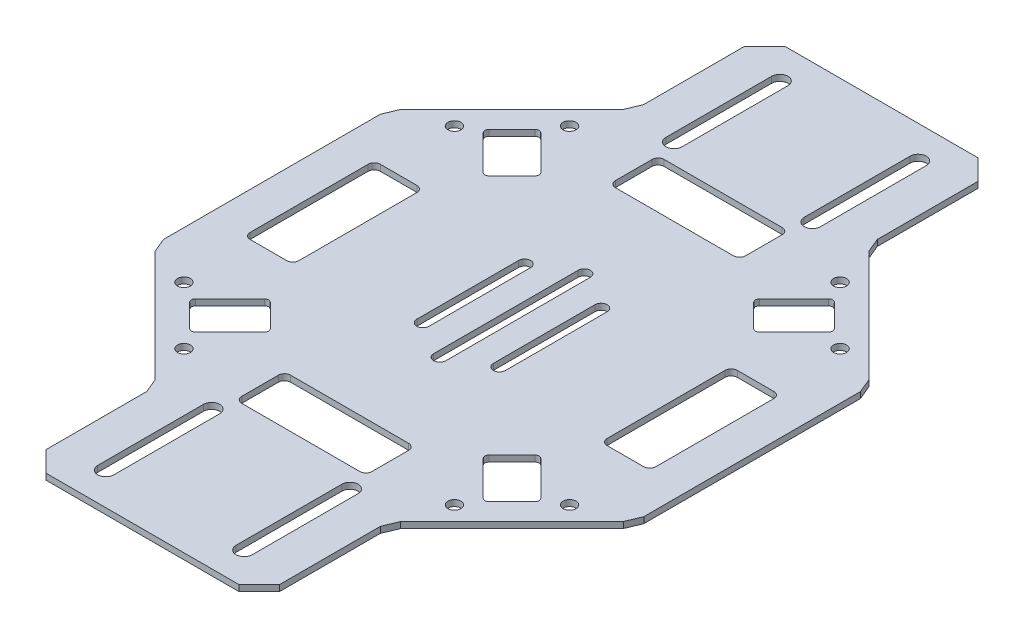
SolidWorks part; units mm, degrees
ref_plane "Front Plane" through (0, 0, 0) normal (0, 0, 1) x (1, 0, 0)
ref_plane "Top Plane" through (0, 0, 0) normal (0, 1, 0) x (1, 0, 0)
ref_plane "Right Plane" through (0, 0, 0) normal (1, 0, 0) x (0, 0, -1)
sketch "Sketch1" plane through (0, 0, 0) normal (0, -1, 0) x (1, 0, 0)
  line L0 (-19, -82.8) -> (-19, -56.8)
  line L1 (-15, -56.8) -> (-15, -82.8)
  line L2 (19, 82.8) -> (19, 56.8)
  line L3 (15, 56.8) -> (15, 82.8)
  line L4 (-15, 82.8) -> (-15, 56.8)
  line L5 (-19, 56.8) -> (-19, 82.8)
  line L6 (-14.5, 51.9) -> (14.5, 51.9)
  line L7 (16, 50.4) -> (16, 41.4)
  line L8 (14.5, 39.9) -> (-14.5, 39.9)
  line L9 (-16, 41.4) -> (-16, 50.4)
  line L10 (16, -41.4) -> (16, -50.4)
  line L11 (14.5, -51.9) -> (-14.5, -51.9)
  line L12 (-16, -50.4) -> (-16, -41.4)
  line L13 (-14.5, -39.9) -> (14.5, -39.9)
  line L14 (19, -56.8) -> (19, -82.8)
  line L15 (15, -82.8) -> (15, -56.8)
  line L16 (-10.9, -12.5) -> (-10.9, 12.5)
  line L17 (-7.9, 12.5) -> (-7.9, -12.5)
  line L18 (10.9, 12.5) -> (10.9, -12.5)
  line L19 (7.9, -12.5) -> (7.9, 12.5)
  line L20 (-32.5269, -26.8701) -> (-26.8701, -32.5269)
  line L21 (-26.8701, -33.9411) -> (-35.3553, -42.4264)
  line L22 (-36.7696, -42.4264) -> (-42.4264, -36.7696)
  line L23 (-42.4264, -35.3553) -> (-33.9411, -26.8701)
  line L24 (-26.8701, 32.5269) -> (-32.5269, 26.8701)
  line L25 (-33.9411, 26.8701) -> (-42.4264, 35.3553)
  line L26 (-42.4264, 36.7696) -> (-36.7696, 42.4264)
  line L27 (-35.3553, 42.4264) -> (-26.8701, 33.9411)
  line L28 (48.35, -16) -> (39.35, -16)
  line L29 (37.85, -14.5) -> (37.85, 14.5)
  line L30 (39.35, 16) -> (48.35, 16)
  line L31 (49.85, 14.5) -> (49.85, -14.5)
  line L32 (-39.35, -16) -> (-48.35, -16)
  line L33 (-49.85, -14.5) -> (-49.85, 14.5)
  line L34 (-48.35, 16) -> (-39.35, 16)
  line L35 (-37.85, 14.5) -> (-37.85, -14.5)
  line L36 (26.8701, -32.5269) -> (32.5269, -26.8701)
  line L37 (33.9411, -26.8701) -> (42.4264, -35.3553)
  line L38 (42.4264, -36.7696) -> (36.7696, -42.4264)
  line L39 (35.3553, -42.4264) -> (26.8701, -33.9411)
  line L40 (32.5269, 26.8701) -> (26.8701, 32.5269)
  line L41 (26.8701, 33.9411) -> (35.3553, 42.4264)
  line L42 (36.7696, 42.4264) -> (42.4264, 36.7696)
  line L43 (42.4264, 35.3553) -> (33.9411, 26.8701)
  line L44 (1.5, 17.75) -> (1.5, -17.75)
  line L45 (-1.5, -17.75) -> (-1.5, 17.75)
  line L46 (-59, 26.6102) -> (-59, -26.6102)
  line L47 (-59, -26.6102) -> (-57.5355, -30.1457)
  line L48 (-57.5355, -30.1457) -> (-30.1645, -57.5168)
  line L49 (-30.1645, -57.5168) -> (-28.7, -61.0523)
  line L50 (-28.7, -61.0523) -> (-28.7, -85.8)
  line L51 (-28.7, -85.8) -> (-23.7, -90.8)
  line L52 (-23.7, -90.8) -> (23.7, -90.8)
  line L53 (23.7, -90.8) -> (28.7, -85.8)
  line L54 (28.7, -85.8) -> (28.7, -61.0523)
  line L55 (28.7, -61.0523) -> (30.1645, -57.5168)
  line L56 (30.1645, -57.5168) -> (57.5355, -30.1457)
  line L57 (57.5355, -30.1457) -> (59, -26.6102)
  line L58 (59, -26.6102) -> (59, 26.6102)
  line L59 (59, 26.6102) -> (57.5355, 30.1457)
  line L60 (57.5355, 30.1457) -> (30.1645, 57.5168)
  line L61 (30.1645, 57.5168) -> (28.7, 61.0523)
  line L62 (28.7, 61.0523) -> (28.7, 85.8)
  line L63 (28.7, 85.8) -> (23.7, 90.8)
  line L64 (23.7, 90.8) -> (-23.7, 90.8)
  line L65 (-23.7, 90.8) -> (-28.7, 85.8)
  line L66 (-28.7, 85.8) -> (-28.7, 61.0523)
  line L67 (-28.7, 61.0523) -> (-30.1645, 57.5168)
  line L68 (-30.1645, 57.5168) -> (-57.5355, 30.1457)
  line L69 (-57.5355, 30.1457) -> (-59, 26.6102)
  line L70 (33.234, 47.3762) -> (47.3762, 33.234) construction
  arc A0 (-15, -82.8) -> (-19, -82.8) centre (-17, -82.8) cw
  arc A1 (-19, -56.8) -> (-15, -56.8) centre (-17, -56.8) cw
  arc A2 (15, 82.8) -> (19, 82.8) centre (17, 82.8) cw
  arc A3 (19, 56.8) -> (15, 56.8) centre (17, 56.8) cw
  arc A4 (-19, 82.8) -> (-15, 82.8) centre (-17, 82.8) cw
  arc A5 (-15, 56.8) -> (-19, 56.8) centre (-17, 56.8) cw
  arc A6 (-16, 50.4) -> (-14.5, 51.9) centre (-14.5, 50.4) cw
  arc A7 (14.5, 51.9) -> (16, 50.4) centre (14.5, 50.4) cw
  arc A8 (16, 41.4) -> (14.5, 39.9) centre (14.5, 41.4) cw
  arc A9 (-14.5, 39.9) -> (-16, 41.4) centre (-14.5, 41.4) cw
  arc A10 (14.5, -39.9) -> (16, -41.4) centre (14.5, -41.4) cw
  arc A11 (16, -50.4) -> (14.5, -51.9) centre (14.5, -50.4) cw
  arc A12 (-14.5, -51.9) -> (-16, -50.4) centre (-14.5, -50.4) cw
  arc A13 (-16, -41.4) -> (-14.5, -39.9) centre (-14.5, -41.4) cw
  arc A14 (15, -56.8) -> (19, -56.8) centre (17, -56.8) cw
  arc A15 (19, -82.8) -> (15, -82.8) centre (17, -82.8) cw
  arc A16 (-7.9, -12.5) -> (-10.9, -12.5) centre (-9.4, -12.5) cw
  arc A17 (-10.9, 12.5) -> (-7.9, 12.5) centre (-9.4, 12.5) cw
  arc A18 (7.9, 12.5) -> (10.9, 12.5) centre (9.4, 12.5) cw
  arc A19 (10.9, -12.5) -> (7.9, -12.5) centre (9.4, -12.5) cw
  arc A20 (-33.9411, -26.8701) -> (-32.5269, -26.8701) centre (-33.234, -27.5772) cw
  arc A21 (-26.8701, -32.5269) -> (-26.8701, -33.9411) centre (-27.5772, -33.234) cw
  arc A22 (-35.3553, -42.4264) -> (-36.7696, -42.4264) centre (-36.0624, -41.7193) cw
  arc A23 (-42.4264, -36.7696) -> (-42.4264, -35.3553) centre (-41.7193, -36.0624) cw
  arc A24 (-26.8701, 33.9411) -> (-26.8701, 32.5269) centre (-27.5772, 33.234) cw
  arc A25 (-32.5269, 26.8701) -> (-33.9411, 26.8701) centre (-33.234, 27.5772) cw
  arc A26 (-42.4264, 35.3553) -> (-42.4264, 36.7696) centre (-41.7193, 36.0624) cw
  arc A27 (-36.7696, 42.4264) -> (-35.3553, 42.4264) centre (-36.0624, 41.7193) cw
  arc A28 (49.85, -14.5) -> (48.35, -16) centre (48.35, -14.5) cw
  arc A29 (39.35, -16) -> (37.85, -14.5) centre (39.35, -14.5) cw
  arc A30 (37.85, 14.5) -> (39.35, 16) centre (39.35, 14.5) cw
  arc A31 (48.35, 16) -> (49.85, 14.5) centre (48.35, 14.5) cw
  arc A32 (-37.85, -14.5) -> (-39.35, -16) centre (-39.35, -14.5) cw
  arc A33 (-48.35, -16) -> (-49.85, -14.5) centre (-48.35, -14.5) cw
  arc A34 (-49.85, 14.5) -> (-48.35, 16) centre (-48.35, 14.5) cw
  arc A35 (-39.35, 16) -> (-37.85, 14.5) centre (-39.35, 14.5) cw
  arc A36 (26.8701, -33.9411) -> (26.8701, -32.5269) centre (27.5772, -33.234) cw
  arc A37 (32.5269, -26.8701) -> (33.9411, -26.8701) centre (33.234, -27.5772) cw
  arc A38 (42.4264, -35.3553) -> (42.4264, -36.7696) centre (41.7193, -36.0624) cw
  arc A39 (36.7696, -42.4264) -> (35.3553, -42.4264) centre (36.0624, -41.7193) cw
  arc A40 (33.9411, 26.8701) -> (32.5269, 26.8701) centre (33.234, 27.5772) cw
  arc A41 (26.8701, 32.5269) -> (26.8701, 33.9411) centre (27.5772, 33.234) cw
  arc A42 (35.3553, 42.4264) -> (36.7696, 42.4264) centre (36.0624, 41.7193) cw
  arc A43 (42.4264, 36.7696) -> (42.4264, 35.3553) centre (41.7193, 36.0624) cw
  arc A44 (-1.5, 17.75) -> (1.5, 17.75) centre (0, 17.75) cw
  arc A45 (1.5, -17.75) -> (-1.5, -17.75) centre (0, -17.75) cw
  circle A46 centre (-33.234, -47.3762) radius 1.6
  circle A47 centre (-47.3762, -33.234) radius 1.6
  circle A48 centre (-47.3762, 33.234) radius 1.6
  circle A49 centre (-33.234, 47.3762) radius 1.6
  circle A50 centre (33.234, 47.3762) radius 1.6
  circle A51 centre (47.3762, 33.234) radius 1.6
  circle A52 centre (47.3762, -33.234) radius 1.6
  circle A53 centre (33.234, -47.3762) radius 1.6
  point P178 (40.3051, 40.3051)
extrude "Boss-Extrude1" add sketch "Sketch1" against normal mid plane 1.5
sketch "Sketch2" plane through (0, 0.75, 0) normal (0, 1, 0) x (1, 0, 0)
  line L0 (33.234, -47.3762) -> (47.3762, -33.234) construction
  line L1 (33.234, -47.3762) -> (47.3762, -33.234) construction
  point P0 (40.3051, -40.3051)
  point P4 (0, 0)
sketch "Sketch3" plane through (0, -0.75, 0) normal (0, -1, 0) x (1, 0, 0)
  line L0 (33.234, 47.3762) -> (47.3762, 33.234) construction
  line L1 (33.234, 47.3762) -> (47.3762, 33.234) construction
  point P0 (40.3051, 40.3051)
  point P4 (40.3051, 40.3051)
